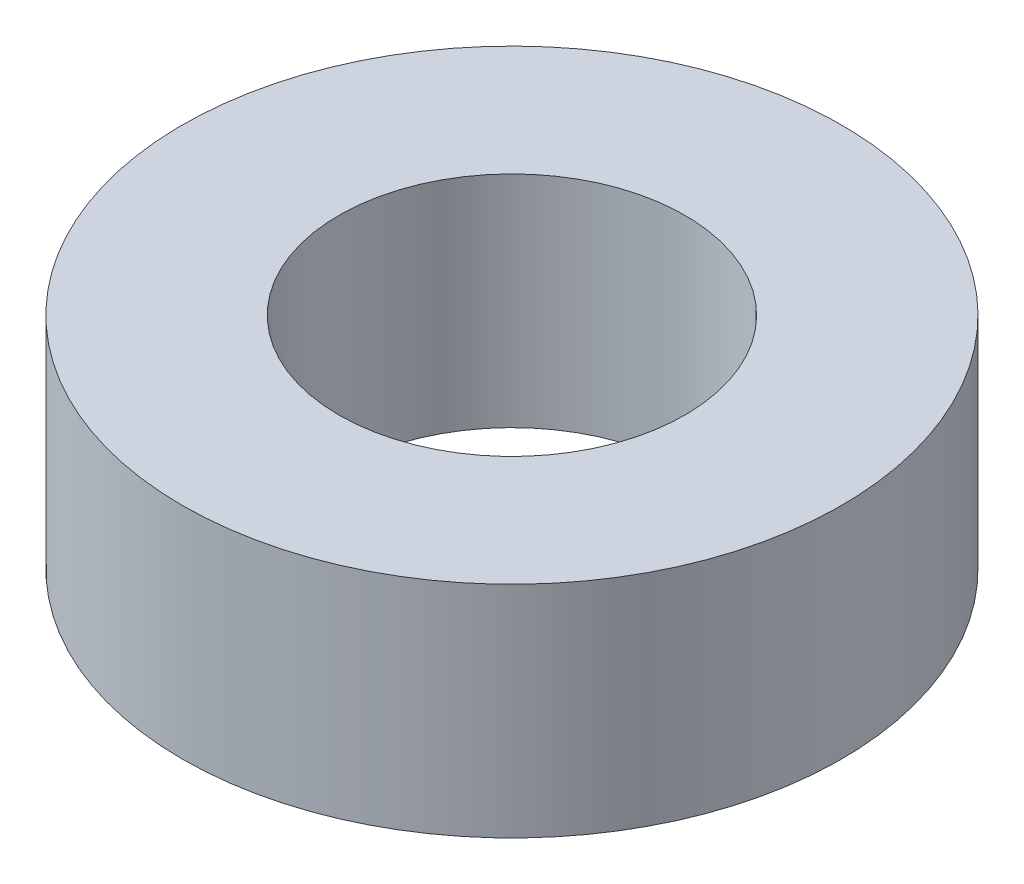
SolidWorks part; units mm, degrees
ref_plane "前视基准面" through (0, 0, 0) normal (0, 0, 1) x (1, 0, 0)
ref_plane "上视基准面" through (0, 0, 0) normal (0, 1, 0) x (1, 0, 0)
ref_plane "右视基准面" through (0, 0, 0) normal (1, 0, 0) x (0, 0, -1)
other "Configuration Table"
sketch "草图1" plane through (0, 0, 0) normal (0, 1, 0) x (1, 0, 0)
  circle A0 centre (0, 0) radius 3.15
  circle A1 centre (0, 0) radius 6
  dimension "D1" = 6.3
  dimension "D2" = 12
extrude "凸台-拉伸1" add sketch "草图1" along normal blind 4
